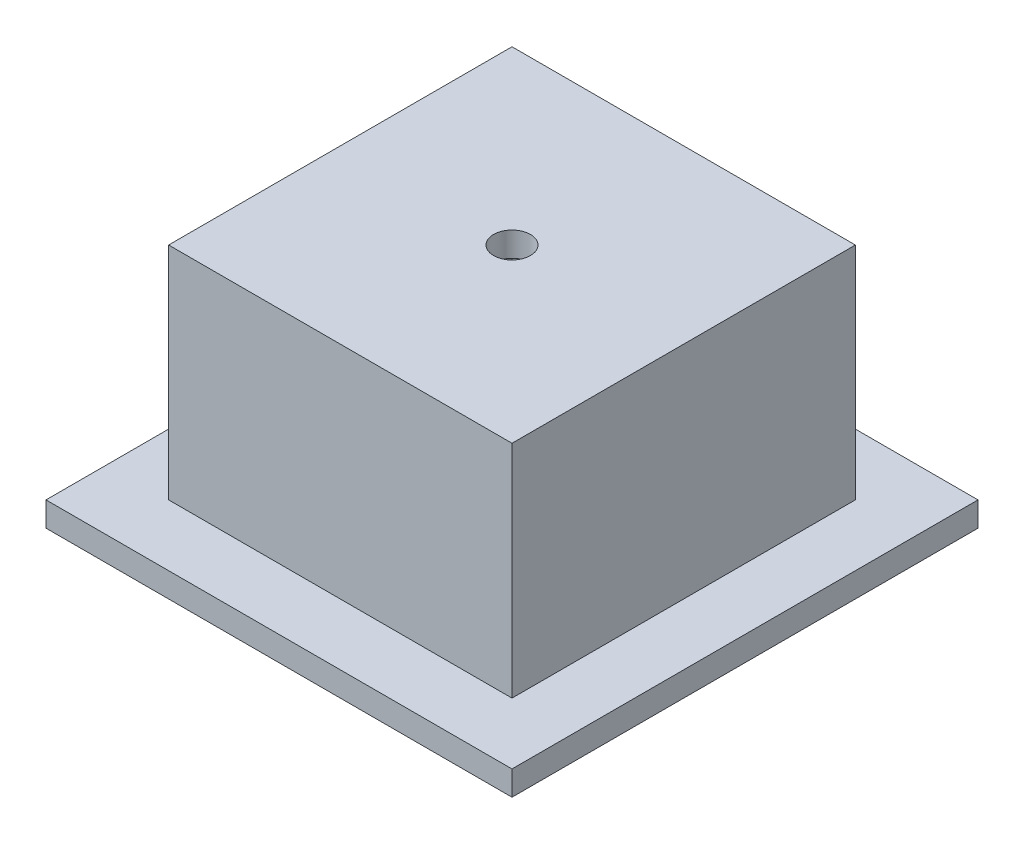
SolidWorks part; units mm, degrees
ref_plane "Front Plane" through (0, 0, 0) normal (0, 0, 1) x (1, 0, 0)
ref_plane "Top Plane" through (0, 0, 0) normal (0, 1, 0) x (1, 0, 0)
ref_plane "Right Plane" through (0, 0, 0) normal (1, 0, 0) x (0, 0, -1)
sketch "Sketch1" plane through (0, 0, 0) normal (0, 1, 0) x (1, 0, 0)
  line L1 (-35.56, 35.56) -> (35.56, 35.56)
  line L2 (-35.56, 35.56) -> (-35.56, -35.56)
  line L3 (-35.56, -35.56) -> (35.56, -35.56)
  line L4 (35.56, 35.56) -> (35.56, -35.56)
  line L5 (-35.56, 35.56) -> (35.56, -35.56) construction
  line L6 (-35.56, -35.56) -> (35.56, 35.56) construction
  point P0 (0, 0)
  dimension "D1" = 71.12
  dimension "D2" = 71.12
extrude "Boss-Extrude1" add sketch "Sketch1" along normal blind 50.8
sketch "Sketch2" plane through (0, 0, 0) normal (0, 1, 0) x (1, 0, 0)
  line L0 (-35.56, 35.56) -> (-35.56, -35.56) construction
  line L1 (-48.26, 48.26) -> (48.26, 48.26)
  line L2 (-48.26, 48.26) -> (-48.26, -48.26)
  line L3 (-48.26, -48.26) -> (48.26, -48.26)
  line L4 (48.26, 48.26) -> (48.26, -48.26)
  line L5 (-48.26, 48.26) -> (48.26, -48.26) construction
  line L6 (-48.26, -48.26) -> (48.26, 48.26) construction
  line L7 (35.56, 35.56) -> (-35.56, 35.56) construction
  point P0 (0, 0)
  dimension "D1" = 12.7
  dimension "D2" = 12.7
extrude "Boss-Extrude2" add sketch "Sketch2" along normal blind 5.08
sketch "Sketch3" plane through (0, 0, 0) normal (0, -1, 0) x (1, 0, 0)
  line L0 (-35.56, -35.56) -> (-35.56, 35.56) construction
  line L1 (-32.385, 32.385) -> (32.385, 32.385)
  line L2 (-32.385, 32.385) -> (-32.385, -32.385)
  line L3 (-32.385, -32.385) -> (32.385, -32.385)
  line L4 (32.385, 32.385) -> (32.385, -32.385)
  line L5 (-32.385, 32.385) -> (32.385, -32.385) construction
  line L6 (-32.385, -32.385) -> (32.385, 32.385) construction
  line L7 (-35.56, 35.56) -> (35.56, 35.56) construction
  point P0 (0, 0)
  dimension "D1" = 3.175
  dimension "D2" = 3.175
extrude "Cut-Extrude1" cut sketch "Sketch3" against normal offset from surface (45.72 mm away) 5.08 up to face at (0, 50.8, 0)
sketch "Sketch4" plane through (0, 50.8, 0) normal (0, 1, 0) x (1, 0, 0)
  circle A0 centre (0, 0) radius 3.81
  dimension "D1" = 7.62
extrude "Cut-Extrude2" cut sketch "Sketch4" against normal through all
